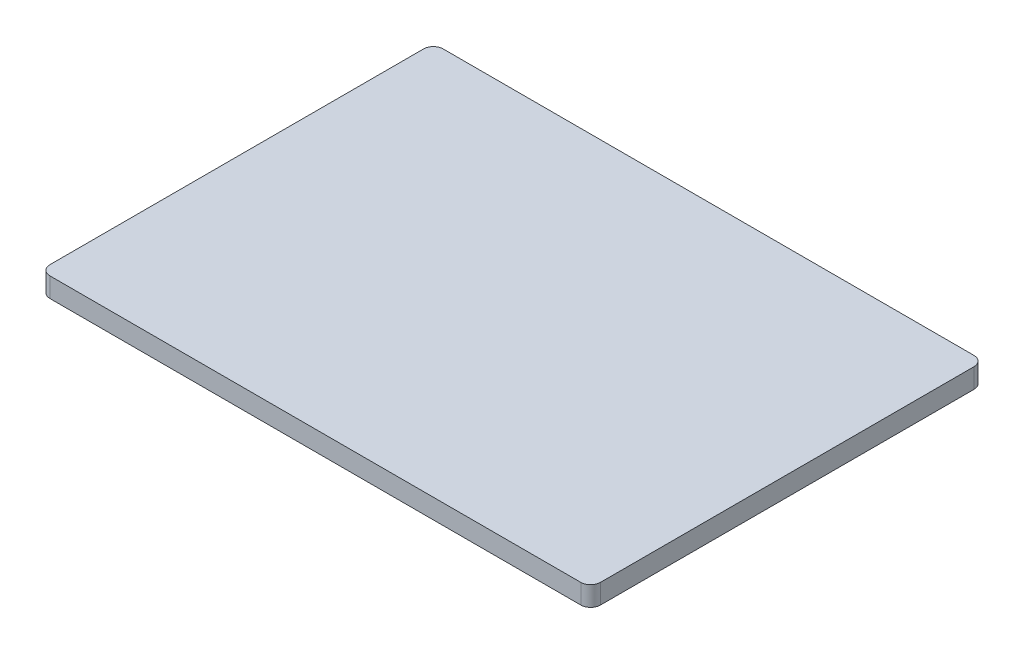
SolidWorks part; units mm, degrees
ref_plane "Front Plane" through (0, 0, 0) normal (0, 0, 1) x (1, 0, 0)
ref_plane "Top Plane" through (0, 0, 0) normal (0, 1, 0) x (1, 0, 0)
ref_plane "Right Plane" through (0, 0, 0) normal (1, 0, 0) x (0, 0, -1)
sketch "Sketch1" plane through (0, 0, 0) normal (0, 1, 0) x (1, 0, 0)
  line L1 (-140, -100) -> (140, -100)
  line L2 (-140, -100) -> (-140, 100)
  line L3 (-140, 100) -> (140, 100)
  line L4 (140, -100) -> (140, 100)
  line L5 (-140, -100) -> (140, 100) construction
  line L6 (-140, 100) -> (140, -100) construction
  point P0 (0, 0)
  dimension "D1" = 280
  dimension "D2" = 200
extrude "Boss-Extrude1" add sketch "Sketch1" along normal mid plane 10
fillet "Fillet1" radius 5 4 edges at (140, 0, 100) (140, 0, -100) (-140, 0, -100) (-140, 0, 100)
